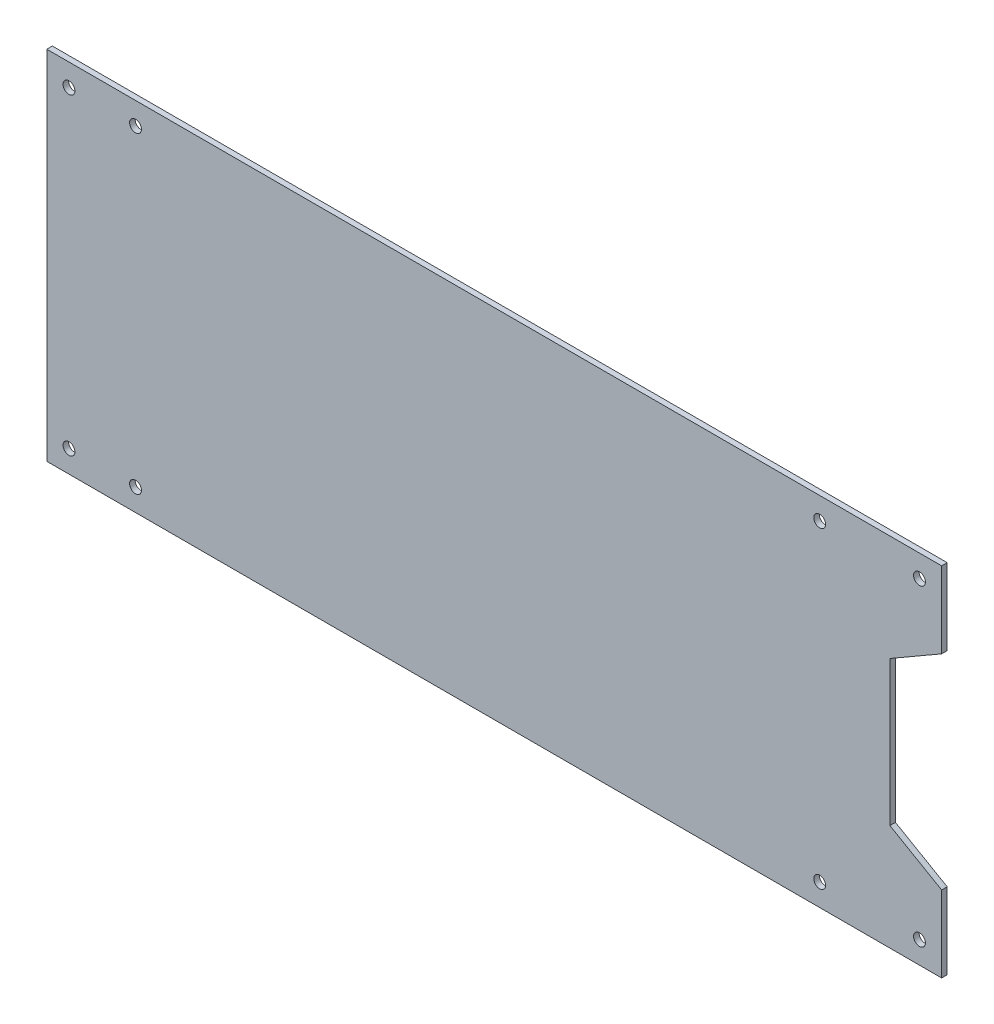
SolidWorks part; units mm, degrees
material "Thornel Mat VMA"
ref_plane "Front Plane" through (0, 0, 0) normal (0, 0, 1) x (1, 0, 0)
ref_plane "Top Plane" through (0, 0, 0) normal (0, 1, 0) x (1, 0, 0)
ref_plane "Right Plane" through (0, 0, 0) normal (1, 0, 0) x (0, 0, -1)
sketch "Sketch1" plane through (0, 0, 0) normal (0, 0, 1) x (1, 0, 0)
  line L4 (-798.4778, 511.53) -> (-798.4778, 608.0809)
  line L5 (-798.4778, 608.0809) -> (-828.4778, 608.0809)
  line L6 (-828.4778, 608.0809) -> (-828.4778, 511.53)
  line L7 (-828.4778, 511.53) -> (-798.4778, 511.53)
  line L9 (-586.414, 608.0809) -> (-828.4778, 608.0809)
  line L10 (-828.4778, 608.0809) -> (-828.4778, 511.53)
  line L11 (-828.4778, 511.53) -> (-586.414, 511.53)
  line L18 (-627.4379, 608.0809) -> (-627.4379, 573.7586)
  line L19 (-627.4379, 555.4283) -> (-627.4379, 536.7817)
  line L20 (-627.4379, 518.4051) -> (-627.4379, 511.53)
  line L21 (-627.4379, 511.53) -> (-586.414, 511.53)
  line L22 (-586.414, 511.53) -> (-586.414, 532.1488)
  line L23 (-586.414, 532.1488) -> (-600.414, 540.2317)
  line L24 (-600.414, 540.2317) -> (-600.414, 579.3792)
  line L25 (-600.414, 579.3792) -> (-586.414, 587.4621)
  line L26 (-586.414, 587.4621) -> (-586.414, 608.0809)
  line L27 (-586.414, 608.0809) -> (-627.4379, 608.0809)
  line L32 (-586.414, 511.53) -> (-586.414, 532.1488)
  line L33 (-586.414, 532.1488) -> (-600.414, 540.2317)
  line L34 (-600.414, 540.2317) -> (-600.414, 579.3792)
  line L35 (-600.414, 579.3792) -> (-586.414, 587.4621)
  line L36 (-586.414, 587.4621) -> (-586.414, 608.0809)
  arc A6 (-630.4378, 569.176) -> (-627.4379, 573.7586) centre (-632.4379, 573.7586) ccw
  arc A7 (-630.4378, 569.176) -> (-630.4378, 560.0109) centre (-628.4378, 564.5934) ccw
  arc A8 (-627.4379, 555.4283) -> (-630.4378, 560.0109) centre (-632.4379, 555.4283) ccw
  arc A9 (-630.4646, 532.1876) -> (-627.4379, 536.7817) centre (-632.4379, 536.7817) ccw
  arc A10 (-630.4646, 532.1876) -> (-630.4646, 522.9993) centre (-628.4914, 527.5934) ccw
  arc A11 (-627.4379, 518.4051) -> (-630.4646, 522.9993) centre (-632.4379, 518.4051) ccw
  dimension "D1" = 0
  dimension "D2" = 0
extrude "Boss-Extrude1" add sketch "Sketch1" along normal blind 1.5
sketch "Sketch2" plane through (0, 0, 1.5) normal (0, 0, 1) x (1, 0, 0)
  line L0 (-586.414, 608.0809) -> (-828.4778, 608.0809) construction
  line L1 (-822.4778, 517.53) -> (-592.414, 517.53) construction
  line L2 (-822.4778, 517.53) -> (-822.4778, 602.0809) construction
  line L3 (-822.4778, 602.0809) -> (-592.414, 602.0809) construction
  line L4 (-592.414, 517.53) -> (-592.414, 602.0809) construction
  line L5 (-828.4778, 511.53) -> (-586.414, 511.53) construction
  line L6 (-828.4778, 608.0809) -> (-828.4778, 511.53) construction
  line L7 (-586.414, 587.4621) -> (-586.414, 608.0809) construction
  line L8 (-804.4778, 602.0809) -> (-804.4778, 517.53) construction
  line L9 (-619.414, 602.0809) -> (-619.414, 517.53) construction
  circle A0 centre (-822.4778, 602.0809) radius 1.6
  circle A1 centre (-804.4778, 602.0809) radius 1.6
  circle A2 centre (-822.4778, 517.53) radius 1.6
  circle A3 centre (-804.4778, 517.53) radius 1.6
  circle A4 centre (-619.414, 602.0809) radius 1.6
  circle A5 centre (-592.414, 602.0809) radius 1.6
  circle A6 centre (-619.414, 517.53) radius 1.6
  circle A7 centre (-592.414, 517.53) radius 1.6
  dimension "D7" = 3.2
  dimension "D1" = 6
  dimension "D2" = 6
  dimension "D3" = 6
  dimension "D4" = 6
  dimension "D5" = 18
  dimension "D6" = 27
extrude "Cut-Extrude1" cut sketch "Sketch2" against normal blind 3.5
